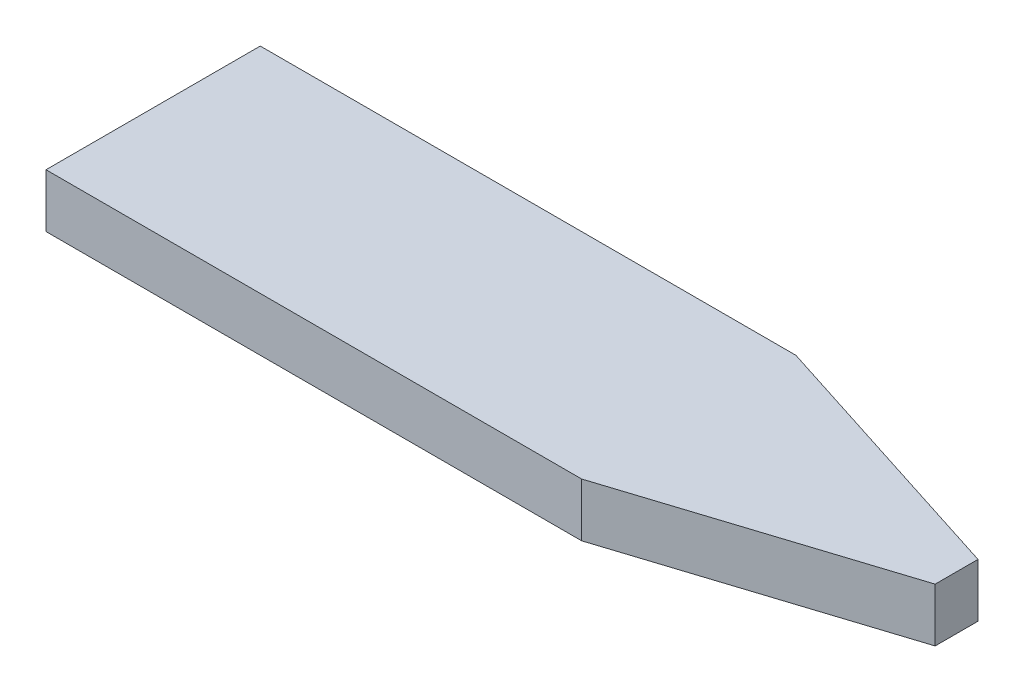
SolidWorks part; units mm, degrees
material "Aleación 1060"
ref_plane "Alzado" through (0, 0, 0) normal (0, 0, 1) x (1, 0, 0)
ref_plane "Planta" through (0, 0, 0) normal (0, 1, 0) x (1, 0, 0)
ref_plane "Vista lateral" through (0, 0, 0) normal (1, 0, 0) x (0, 0, -1)
sketch "Croquis1" plane through (0, 0, 0) normal (0, 1, 0) x (1, 0, 0)
  line L0 (0, 0) -> (50, 0) construction
  line L1 (25, 10) -> (-25, 10)
  line L2 (25, 10) -> (25, -10)
  line L3 (25, -10) -> (-25, -10)
  line L4 (-25, 10) -> (-25, -10)
  line L5 (25, 10) -> (-25, -10) construction
  line L6 (25, -10) -> (-25, 10) construction
  line L7 (50, 0) -> (50, 2)
  line L8 (50, 0) -> (50, -2)
  line L9 (50, -2) -> (25, -10)
  line L10 (25, 10) -> (50, 2)
  point P0 (0, 0)
  dimension "D1" = 20
  dimension "D2" = 50
  dimension "D3" = 50
  dimension "D4" = 2
extrude "Saliente-Extruir1" add sketch "Croquis1" along normal blind 5 contours L1 L4 L3 L2 | L10 L2 L9 L8 L7
